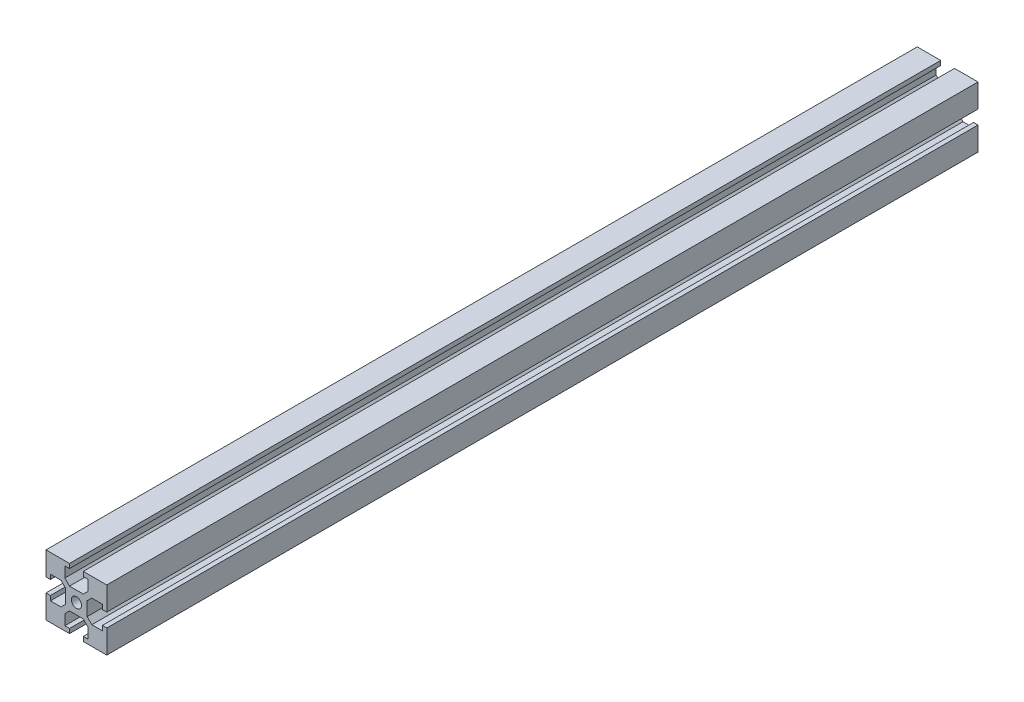
SolidWorks part; units mm, degrees
ref_plane "正面" through (0, 0, 0) normal (0, 0, 1) x (1, 0, 0)
ref_plane "平面" through (0, 0, 0) normal (0, 1, 0) x (1, 0, 0)
ref_plane "右側面" through (0, 0, 0) normal (1, 0, 0) x (0, 0, -1)
sketch "ｽｹｯﾁ2" plane through (0, 0, 0) normal (0, 0, 1) x (1, 0, 0)
  line L0 (0, 0) -> (0, 7.5) construction
  line L1 (-7.5, -7.5) -> (7.5, -7.5) construction
  line L2 (-7.5, -7.5) -> (-7.5, 7.5) construction
  line L3 (-7.5, 7.5) -> (7.5, 7.5) construction
  line L4 (7.5, -7.5) -> (7.5, 7.5) construction
  line L5 (-7.5, -7.5) -> (7.5, 7.5) construction
  line L6 (-7.5, 7.5) -> (7.5, -7.5) construction
  line L8 (1.7, 2.65) -> (-1.7, 2.65)
  line L9 (-2.85, 3.8) -> (2.85, 3.8) construction
  line L10 (-2.85, 6.4) -> (-2.85, 3.8)
  line L11 (2.85, 6.4) -> (2.85, 3.8)
  line L12 (-2.85, 3.8) -> (-1.7, 2.65)
  line L13 (1.7, 2.65) -> (2.85, 3.8)
  line L14 (-2.85, 6.4) -> (-1.7, 6.4)
  line L15 (-1.7, 6.4) -> (-1.7, 7.5)
  line L16 (-1.7, 7.5) -> (-7.5, 7.5)
  line L17 (2.85, 6.4) -> (1.7, 6.4)
  line L18 (1.7, 6.4) -> (1.7, 7.5)
  line L19 (1.7, 7.5) -> (7.5, 7.5)
  line L20 (3.8, 2.85) -> (2.65, 1.7)
  line L21 (2.65, -1.7) -> (2.65, 1.7)
  line L22 (2.65, -1.7) -> (3.8, -2.85)
  line L23 (6.4, -2.85) -> (6.4, -1.7)
  line L24 (6.4, -2.85) -> (3.8, -2.85)
  line L25 (6.4, -1.7) -> (7.5, -1.7)
  line L26 (7.5, -1.7) -> (7.5, -7.5)
  line L27 (6.4, 1.7) -> (7.5, 1.7)
  line L28 (7.5, 1.7) -> (7.5, 7.5)
  line L29 (6.4, 2.85) -> (6.4, 1.7)
  line L30 (6.4, 2.85) -> (3.8, 2.85)
  line L31 (2.85, -3.8) -> (1.7, -2.65)
  line L32 (-1.7, -2.65) -> (1.7, -2.65)
  line L33 (-1.7, -2.65) -> (-2.85, -3.8)
  line L34 (-2.85, -6.4) -> (-1.7, -6.4)
  line L35 (-2.85, -6.4) -> (-2.85, -3.8)
  line L36 (-1.7, -6.4) -> (-1.7, -7.5)
  line L37 (-1.7, -7.5) -> (-7.5, -7.5)
  line L38 (1.7, -6.4) -> (1.7, -7.5)
  line L39 (1.7, -7.5) -> (7.5, -7.5)
  line L40 (2.85, -6.4) -> (1.7, -6.4)
  line L41 (2.85, -6.4) -> (2.85, -3.8)
  line L42 (-3.8, -2.85) -> (-2.65, -1.7)
  line L43 (-2.65, 1.7) -> (-2.65, -1.7)
  line L44 (-2.65, 1.7) -> (-3.8, 2.85)
  line L45 (-6.4, 2.85) -> (-6.4, 1.7)
  line L46 (-6.4, 2.85) -> (-3.8, 2.85)
  line L47 (-6.4, 1.7) -> (-7.5, 1.7)
  line L48 (-7.5, 1.7) -> (-7.5, 7.5)
  line L49 (-6.4, -1.7) -> (-7.5, -1.7)
  line L50 (-7.5, -1.7) -> (-7.5, -7.5)
  line L51 (-6.4, -2.85) -> (-6.4, -1.7)
  line L52 (-6.4, -2.85) -> (-3.8, -2.85)
  circle A0 centre (0, 0) radius 1.25
  point P0 (0, 0)
  point P11 (0, 7.5)
  point P14 (0, 2.65)
  point P17 (0, 3.8)
  dimension "D8" = 2.5
  dimension "D1" = 15
  dimension "D2" = 3.4
  dimension "D3" = 1.1
  dimension "D4" = 2.6
  dimension "D5" = 5.7
  dimension "D6" = 3.4
  dimension "D7" = 4
extrude "ﾎﾞｽ - 押し出し1" add sketch "ｽｹｯﾁ2" along normal blind 215
